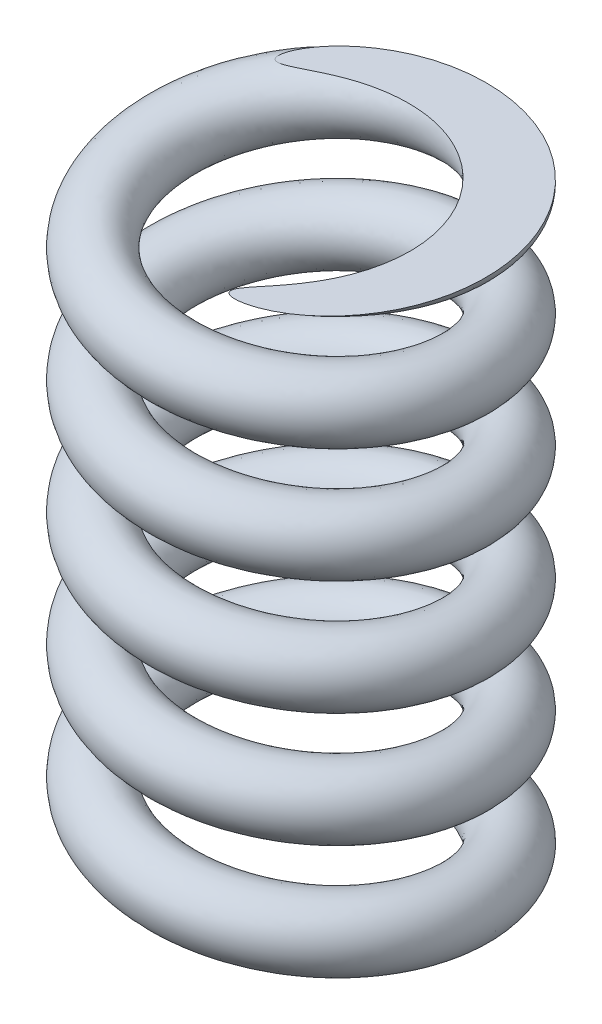
SolidWorks part; units mm, degrees
ref_plane "Спереди" through (0, 0, 0) normal (0, 0, 1) x (1, 0, 0)
ref_plane "Сверху" through (0, 0, 0) normal (0, 1, 0) x (1, 0, 0)
ref_plane "Справа" through (0, 0, 0) normal (1, 0, 0) x (0, 0, -1)
sketch "Эскиз1" plane through (0, 0, 0) normal (0, 1, 0) x (1, 0, 0)
  circle A0 centre (0, 0) radius 4.5
  dimension "D1" = 9
curve "Спираль1" pitch 3.5 height 19 turns 5.4286
sweep "По траектории5" add path "Спираль1" circular profile diameter 2 parameters "D3"=2
sketch "Эскиз89" plane through (0, 0, 0) normal (0, 0, 1) x (1, 0, 0)
  line L1 (18.161, 0) -> (-28.8383, 0)
  line L2 (18.161, 0) -> (18.161, 18)
  line L3 (18.161, 18) -> (-28.8383, 18)
  line L4 (-28.8383, 0) -> (-28.8383, 18)
  line L5 (32.1682, -7.2464) -> (-37.8099, -7.2464)
  line L6 (32.1682, -7.2464) -> (32.1682, 24.7039)
  line L7 (32.1682, 24.7039) -> (-37.8099, 24.7039)
  line L8 (-37.8099, -7.2464) -> (-37.8099, 24.7039)
  dimension "D1" = 18
extrude "Вырез-Вытянуть2" cut sketch "Эскиз89" against normal through all both and the other way through all contours L8 L5 L6 L7 L1 L4 L3 L2
